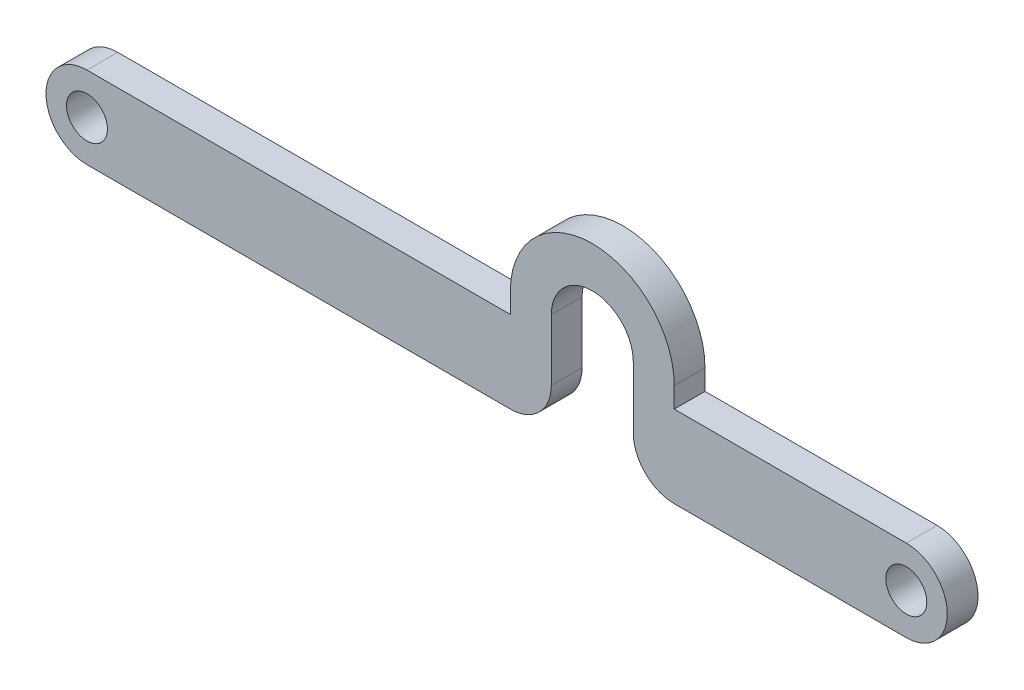
SolidWorks part; units mm, degrees
material "Zoltek Panex 33"
ref_plane "前视基准面" through (0, 0, 0) normal (0, 0, 1) x (1, 0, 0)
ref_plane "上视基准面" through (0, 0, 0) normal (0, 1, 0) x (1, 0, 0)
ref_plane "右视基准面" through (0, 0, 0) normal (1, 0, 0) x (0, 0, -1)
sketch "草图1" plane through (0, 0, 0) normal (0, 0, 1) x (1, 0, 0)
  line L0 (28.6708, 2) -> (40, 2)
  line L1 (0, 0) -> (40, 0) construction
  line L2 (0, 2) -> (20.6708, 2)
  line L3 (0, -2) -> (20.6708, -2)
  line L4 (28.6708, 0) -> (28.6708, 3) construction
  line L6 (26.6708, 0) -> (26.6708, 3)
  line L8 (28.6708, 3) -> (28.6708, 2)
  line L9 (22.6708, 3) -> (22.6708, 0)
  line L10 (20.6708, 3) -> (20.6708, 2)
  line L11 (28.6708, -2) -> (40, -2)
  arc A1 (0, 2) -> (0, -2) centre (0, 0) ccw
  arc A2 (40, -2) -> (40, 2) centre (40, 0) ccw
  circle A3 centre (40, 0) radius 1
  circle A4 centre (0, 0) radius 1
  arc A5 (26.6708, 3) -> (22.6708, 3) centre (24.6708, 3) ccw
  arc A7 (28.6708, 3) -> (20.6708, 3) centre (24.6708, 3) ccw
  arc A8 (28.6708, -2) -> (26.6708, 0) centre (28.6708, 0) cw
  arc A9 (22.6708, 0) -> (20.6708, -2) centre (20.6708, 0) cw
  dimension "D1" = 2
  dimension "D3" = 2
  dimension "D4" = 2
  dimension "D5" = 15.62
  dimension "D6" = 4
  dimension "D7" = 2
  dimension "D8" = 4
  dimension "D2" = 40
  dimension "D9" = 1
extrude "凸台-拉伸1" add sketch "草图1" along normal blind 1.5
